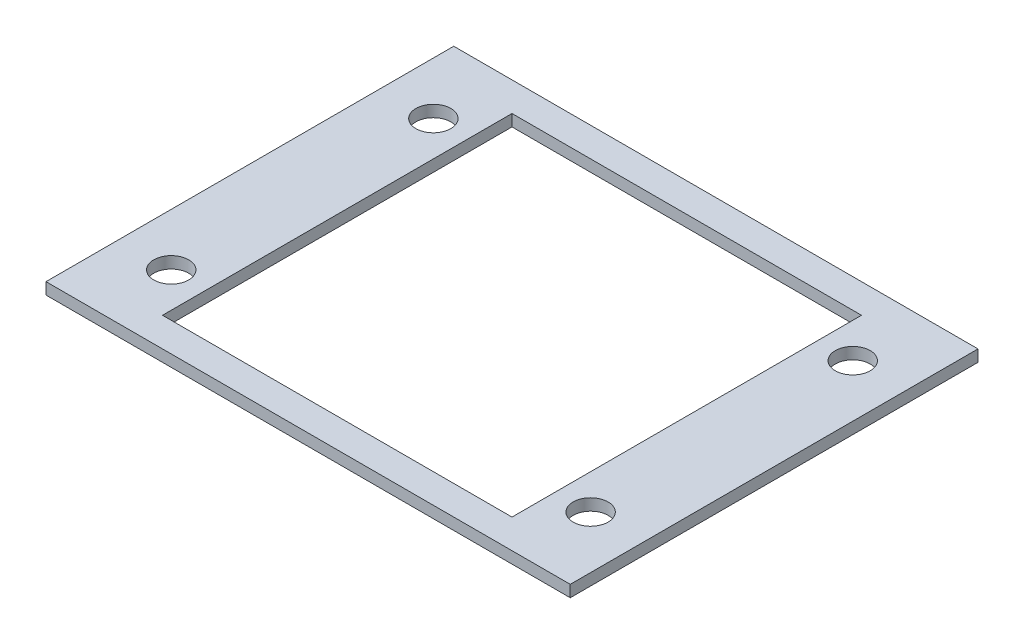
SolidWorks part; units mm, degrees
ref_plane "Alzado" through (0, 0, 0) normal (0, 0, 1) x (1, 0, 0)
ref_plane "Planta" through (0, 0, 0) normal (0, 1, 0) x (1, 0, 0)
ref_plane "Vista lateral" through (0, 0, 0) normal (1, 0, 0) x (0, 0, -1)
sketch "Croquis1" plane through (0, 0, 0) normal (0, 1, 0) x (1, 0, 0)
  line L0 (0, 0) -> (30, 30) construction
  line L1 (0, 0) -> (30, 0)
  line L2 (0, 0) -> (0, 30)
  line L3 (0, 30) -> (30, 30)
  line L4 (30, 0) -> (30, 30)
  line L5 (-7.5, -7.5) -> (37.5, -7.5)
  line L6 (-7.5, -7.5) -> (-7.5, 37.5)
  line L7 (-7.5, 37.5) -> (37.5, 37.5)
  line L8 (37.5, -7.5) -> (37.5, 37.5)
  line L9 (-7.5, 37.5) -> (37.5, -7.5) construction
  line L10 (-9.9749, 39.9749) -> (-7.5, 37.5) construction
  line L11 (33, 15) -> (37.5, 15) construction
  line L12 (15, 15) -> (15, -17.4738) construction
  line L13 (15, 15) -> (0, 15) construction
  line L14 (15, 30) -> (15, 37.5) construction
  line L15 (0, 30) -> (30, 30) construction
  line L16 (0, 30) -> (0, 0) construction
  line L17 (0, 0) -> (30, 0) construction
  line L18 (30, 30) -> (30, 0) construction
  line L19 (0, 30) -> (30, 0) construction
  line L20 (0, 0) -> (30, 30) construction
  line L21 (33, 3.75) -> (33, 15) construction
  line L22 (33, 15) -> (33, 26.25) construction
  line L23 (8, 32.5) -> (15, 32.5) construction
  line L24 (15, 32.5) -> (22, 32.5) construction
  circle A4 centre (-3, 26.25) radius 1.5
  circle A5 centre (-3, 3.75) radius 1.5
  arc A12 (-7.5, -7.3985) -> (-7.3985, -7.5) centre (-4.9749, -4.9749) ccw
  circle A23 centre (33, 26.25) radius 1.5
  circle A24 centre (33, 3.75) radius 1.5
  point P9 (15, 15)
  point P10 (15, 15)
  dimension "D3" = 18
  dimension "D9" = 3
  dimension "D1" = 30
  dimension "D2" = 45
  dimension "D5" = 3.5
  dimension "D6" = 7
  dimension "D8" = 30
  dimension "D10" = 11.25
  dimension "D7" = 17.5
extrude "Saliente-Extruir1" add sketch "Croquis1" along normal blind 1
sketch "Croquis2" plane through (0, 1, 0) normal (0, 1, 0) x (1, 0, 0)
  line L0 (37.5, -7.5) -> (37.5, 37.5) construction
  line L1 (-7.5, 37.5) -> (37.5, 37.5)
  line L2 (-7.5, 37.5) -> (-7.5, 32.5)
  line L3 (-7.5, 32.5) -> (37.5, 32.5)
  line L4 (37.5, 37.5) -> (37.5, 32.5)
  line L5 (-7.5, -7.3985) -> (-7.5, 37.5) construction
  line L10 (37.5, -7.5) -> (-7.5, -7.5)
  line L11 (37.5, -7.5) -> (37.5, -2.5)
  line L12 (37.5, -2.5) -> (-7.5, -2.5)
  line L13 (-7.5, -7.5) -> (-7.5, -2.5)
  dimension "D1" = 5
extrude "Cortar-Extruir1" cut sketch "Croquis2" against normal blind 10
